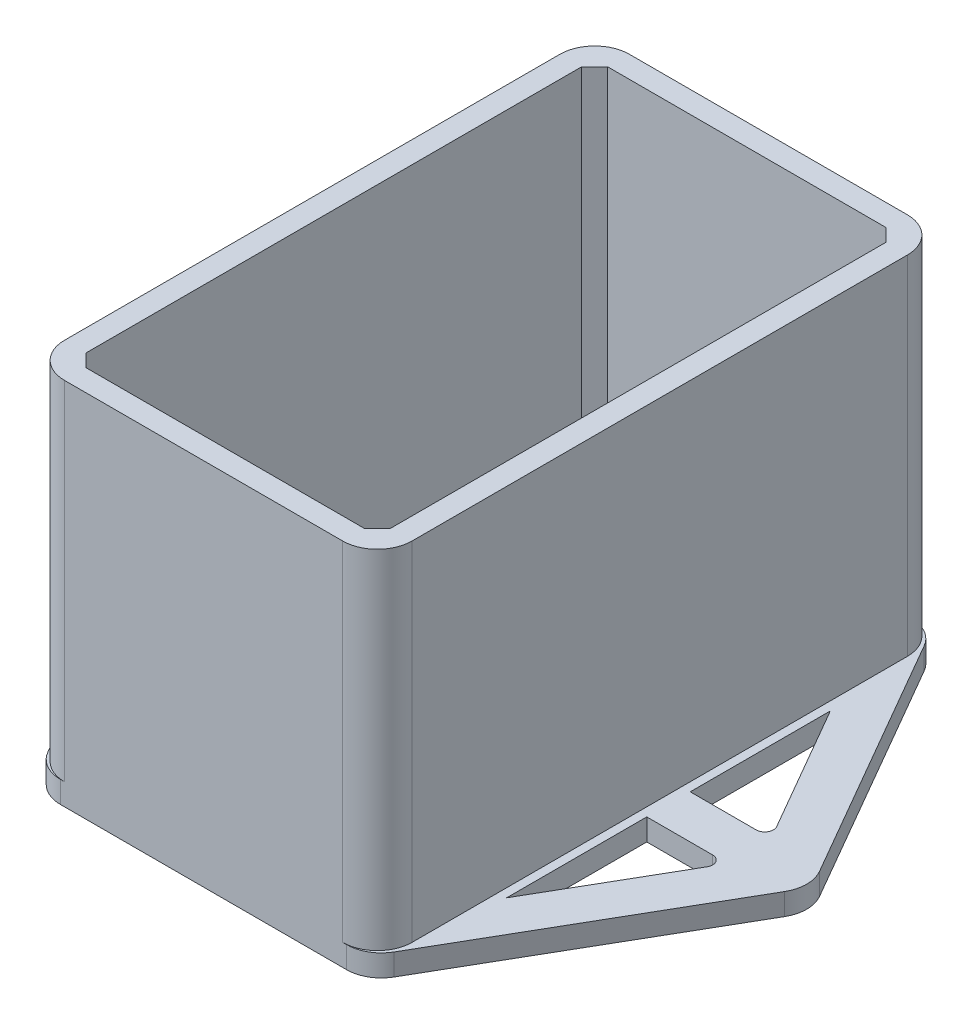
SolidWorks part; units mm, degrees
ref_plane "Front Plane" through (0, 0, 0) normal (0, 0, 1) x (1, 0, 0)
ref_plane "Top Plane" through (0, 0, 0) normal (0, 1, 0) x (1, 0, 0)
ref_plane "Right Plane" through (0, 0, 0) normal (1, 0, 0) x (0, 0, -1)
sketch "Sketch1" plane through (0, 0, 0) normal (0, 1, 0) x (1, 0, 0)
  line L1 (-75.0555, 0) -> (-37.5278, -65)
  line L2 (-37.5278, -65) -> (37.5278, -65)
  line L3 (37.5278, -65) -> (75.0555, 0)
  line L4 (75.0555, 0) -> (37.5278, 65)
  line L5 (37.5278, 65) -> (-37.5278, 65)
  line L6 (-37.5278, 65) -> (-75.0555, 0)
  circle A0 centre (0, 0) radius 65 construction
  circle A1 centre (0, 0) radius 50 construction
  dimension "D2" = 100
  dimension "D1" = 130
extrude "Boss-Extrude1" add sketch "Sketch1" along normal blind 5
fillet "Fillet1" radius 8 6 edges at (37.5278, 2.5, -65) (75.0555, 2.5, 0) (37.5278, 2.5, 65) (-37.5278, 2.5, 65) (-75.0555, 2.5, 0) (-37.5278, 2.5, -65)
sketch "Sketch3" plane through (0, 5, 0) normal (0, 1, 0) x (1, 0, 0)
  line L0 (-32.909, -65) -> (32.909, -65) construction
  line L1 (-32, 65) -> (32, 65)
  line L2 (-40, 57) -> (-40, -57)
  line L3 (-32, -65) -> (32, -65)
  line L4 (40, 57) -> (40, -57)
  line L5 (-40, 65) -> (40, -65) construction
  line L6 (-40, -65) -> (40, 65) construction
  arc A0 (40, 57) -> (32, 65) centre (32, 57) ccw
  arc A1 (40, -57) -> (32, -65) centre (32, -57) cw
  arc A2 (-32, -65) -> (-40, -57) centre (-32, -57) cw
  arc A3 (-32, 65) -> (-40, 57) centre (-32, 57) ccw
  point P0 (0, 0)
  dimension "D1" = 8
  dimension "D2" = 64
extrude "Boss-Extrude2" add sketch "Sketch3" along normal blind 80
sketch "Sketch4" plane through (0, 85, 0) normal (0, 1, 0) x (1, 0, 0)
  line L0 (-35, 57) -> (-32, 60)
  line L1 (32, 60) -> (35, 57)
  line L2 (35, -57) -> (32, -60)
  line L3 (-35, -57) -> (-32, -60)
  line L9 (-32, -60) -> (32, -60)
  line L10 (35, -57) -> (35, 57)
  line L11 (32, 60) -> (-32, 60)
  line L12 (-35, 57) -> (-35, -57)
  line L13 (-32, -60) -> (32, -60)
  line L14 (35, -57) -> (35, 57)
  line L15 (32, 60) -> (-32, 60)
  line L16 (-35, 57) -> (-35, -57)
  arc A9 (-35, -57) -> (-32, -60) centre (-32, -57) ccw
  arc A10 (32, -60) -> (35, -57) centre (32, -57) ccw
  arc A11 (35, 57) -> (32, 60) centre (32, 57) ccw
  arc A12 (-32, 60) -> (-35, 57) centre (-32, 57) ccw
  dimension "D1" = 5
extrude "Cut-Extrude1" cut sketch "Sketch4" against normal up to surface (85 mm away) up to face at (0, 0, 0)
sketch "Sketch8" plane through (0, 0, 0) normal (0, 1, 0) x (1, 0, 0)
  line L0 (0, 40) -> (0, 25) construction
  line L1 (0, 55) -> (0, 65) construction
  line L2 (9.5263, 26.5) -> (24.2487, 52) construction
  line L3 (22.5167, 55) -> (-22.5167, 55) construction
  line L4 (-24.2487, 52) -> (-9.5263, 26.5) construction
  line L5 (-12.5, 0) -> (-62.3346, 0) construction
  line L36 (6.9282, 25) -> (-6.9282, 25) construction
  line L37 (27.7128, 5) -> (57.1577, 5) construction
  line L38 (58.8897, 8) -> (36.3731, 47) construction
  line L39 (32.909, 47) -> (18.1865, 21.5) construction
  line L40 (25.1147, 6.5) -> (18.1865, 18.5) construction
  line L41 (18.1865, -21.5) -> (32.909, -47) construction
  line L42 (36.3731, -47) -> (58.8897, -8) construction
  line L43 (57.1577, -5) -> (27.7128, -5) construction
  line L44 (18.1865, -18.5) -> (25.1147, -6.5) construction
  line L45 (-9.5263, -26.5) -> (-24.2487, -52) construction
  line L46 (-22.5167, -55) -> (22.5167, -55) construction
  line L47 (24.2487, -52) -> (9.5263, -26.5) construction
  line L48 (-6.9282, -25) -> (6.9282, -25) construction
  line L49 (-27.7128, -5) -> (-57.1577, -5) construction
  line L50 (-58.8897, -8) -> (-36.3731, -47) construction
  line L51 (-32.909, -47) -> (-18.1865, -21.5) construction
  line L52 (-25.1147, -6.5) -> (-18.1865, -18.5) construction
  line L53 (-18.1865, 21.5) -> (-32.909, 47) construction
  line L54 (-42, 37.2539) -> (-58.8897, 8)
  line L55 (-57.1577, 5) -> (-42, 5)
  line L56 (-18.1865, 18.5) -> (-25.1147, 6.5) construction
  line L57 (-42, 5) -> (-42, 37.2539)
  line L58 (-40, 57) -> (-40, -57) construction
  line L59 (-40, 57) -> (-40, -57) construction
  line L60 (-36.3731, 47) -> (-42, 37.2539) construction
  line L61 (-42, 5) -> (-27.7128, 5) construction
  line L62 (-42, -5) -> (-42, -37.2539)
  line L63 (-57.1577, -5) -> (-42, -5)
  line L64 (-42, -37.2539) -> (-58.8897, -8)
  line L65 (42, -37.2539) -> (58.8897, -8)
  line L66 (57.1577, -5) -> (42, -5)
  line L67 (42, -5) -> (42, -37.2539)
  line L68 (42, 5) -> (42, 37.2539)
  line L69 (57.1577, 5) -> (42, 5)
  line L70 (42, 37.2539) -> (58.8897, 8)
  circle A0 centre (0, 0) radius 12.5 construction
  circle A1 centre (0, 40) radius 15 construction
  arc A3 (-22.5167, 55) -> (-24.2487, 52) centre (-22.5167, 53) ccw
  arc A4 (24.2487, 52) -> (22.5167, 55) centre (22.5167, 53) ccw construction
  arc A5 (6.9282, 25) -> (9.5263, 26.5) centre (6.9282, 28) ccw construction
  arc A6 (-6.9282, 25) -> (-9.5263, 26.5) centre (-6.9282, 28) cw construction
  arc A7 (25.1147, 6.5) -> (27.7128, 5) centre (27.7128, 8) ccw construction
  arc A8 (57.1577, 5) -> (58.8897, 8) centre (57.1577, 7) ccw construction
  arc A9 (36.3731, 47) -> (32.909, 47) centre (34.641, 46) ccw construction
  arc A10 (18.1865, 18.5) -> (18.1865, 21.5) centre (20.7846, 20) cw construction
  arc A11 (18.1865, -18.5) -> (18.1865, -21.5) centre (20.7846, -20) ccw construction
  arc A12 (32.909, -47) -> (36.3731, -47) centre (34.641, -46) ccw construction
  arc A13 (58.8897, -8) -> (57.1577, -5) centre (57.1577, -7) ccw construction
  arc A14 (25.1147, -6.5) -> (27.7128, -5) centre (27.7128, -8) cw construction
  arc A15 (-6.9282, -25) -> (-9.5263, -26.5) centre (-6.9282, -28) ccw construction
  arc A16 (-24.2487, -52) -> (-22.5167, -55) centre (-22.5167, -53) ccw construction
  arc A17 (22.5167, -55) -> (24.2487, -52) centre (22.5167, -53) ccw construction
  arc A18 (6.9282, -25) -> (9.5263, -26.5) centre (6.9282, -28) cw construction
  arc A19 (-25.1147, -6.5) -> (-27.7128, -5) centre (-27.7128, -8) ccw construction
  arc A20 (-57.1577, -5) -> (-58.8897, -8) centre (-57.1577, -7) ccw construction
  arc A21 (-36.3731, -47) -> (-32.909, -47) centre (-34.641, -46) ccw construction
  arc A22 (-18.1865, -18.5) -> (-18.1865, -21.5) centre (-20.7846, -20) cw construction
  arc A23 (-18.1865, 18.5) -> (-18.1865, 21.5) centre (-20.7846, 20) ccw construction
  arc A24 (-32.909, 47) -> (-36.3731, 47) centre (-34.641, 46) ccw construction
  arc A25 (-58.8897, 8) -> (-57.1577, 5) centre (-57.1577, 7) ccw
  arc A26 (-25.1147, 6.5) -> (-27.7128, 5) centre (-27.7128, 8) cw construction
  arc A27 (-58.8897, -8) -> (-57.1577, -5) centre (-57.1577, -7) cw
  arc A28 (57.1577, -5) -> (58.8897, -8) centre (57.1577, -7) cw construction
  arc A29 (58.8897, -8) -> (57.1577, -5) centre (57.1577, -7) ccw
  arc A30 (58.8897, 8) -> (57.1577, 5) centre (57.1577, 7) cw
  point P19 (0, 25)
  point P30 (0, 0)
  point P66 (0, 0)
  point P88 (0, 0)
  dimension "D1" = 25
  dimension "D3" = 30
  dimension "D6" = 2
  dimension "D8" = 3
  dimension "D2" = 40
  dimension "D4" = 10
  dimension "D5" = 15
  dimension "D7" = 25
  dimension "D9" = 2
  dimension "D10" = 6
extrude "Cut-Extrude2" cut sketch "Sketch8" along normal up to surface (5 mm away) contours A30 L70 L68 L69 | L65 A29 L66 L67 | A27 L64 L62 L63 | L54 A25 L55 L57 up to face at (-44.0442, 5, 0)
